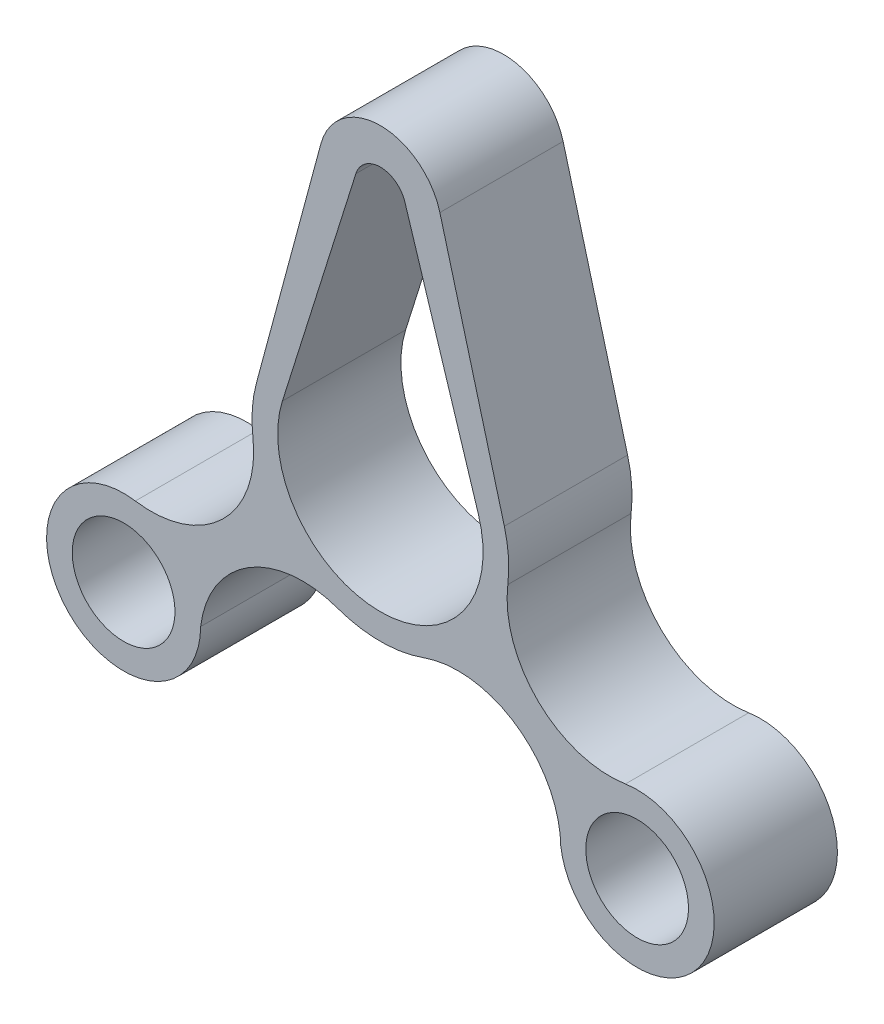
SolidWorks part; units mm, degrees
material "AISI 304"
ref_plane "Front Plane" through (0, 0, 0) normal (0, 0, 1) x (1, 0, 0)
ref_plane "Top Plane" through (0, 0, 0) normal (0, 1, 0) x (1, 0, 0)
ref_plane "Right Plane" through (0, 0, 0) normal (1, 0, 0) x (0, 0, -1)
sketch "Sketch1" plane through (0, 0, 0) normal (0, 0, 1) x (1, 0, 0)
  line L0 (0, 0) -> (0, 50) construction
  line L1 (24.1402, 6.5) -> (11.5873, 53.12)
  line L2 (4.7697, 51.5) -> (19.0788, 6)
  line L3 (-4.7697, 51.5) -> (-19.0788, 6)
  line L4 (-24.1402, 6.5) -> (-11.5873, 53.12)
  arc A0 (-19.0788, 6) -> (19.0788, 6) centre (0, 0) ccw
  arc A1 (-8.412, -23.5423) -> (8.412, -23.5423) centre (0, 0) ccw
  circle A2 centre (50, -40) radius 10
  arc A3 (35, -40) -> (47.7174, -25.1747) centre (50, -40) ccw
  arc A4 (47.7174, -25.1747) -> (24.8188, -3.0042) centre (44.6739, -5.4076) cw
  arc A5 (8.412, -23.5423) -> (35, -40) centre (15.1416, -42.3761) cw
  arc A6 (11.5873, 53.12) -> (-11.5873, 53.12) centre (0, 50) ccw
  arc A7 (4.7697, 51.5) -> (-4.7697, 51.5) centre (0, 50) ccw
  arc A8 (24.8188, -3.0042) -> (24.1402, 6.5) centre (0, 0) ccw
  arc A9 (-24.8188, -3.0042) -> (-24.1402, 6.5) centre (0, 0) cw
  arc A10 (-8.412, -23.5423) -> (-35, -40) centre (-15.1416, -42.3761) ccw
  arc A11 (-47.7174, -25.1747) -> (-24.8188, -3.0042) centre (-44.6739, -5.4076) ccw
  arc A12 (-35, -40) -> (-47.7174, -25.1747) centre (-50, -40) cw
  circle A13 centre (-50, -40) radius 10
  point P14 (0, 0)
  point P16 (25.8904, -0.2118)
  dimension "D3" = 12
  dimension "D4" = 5
  dimension "D5" = 25
  dimension "D6" = 20
  dimension "D7" = 20
  dimension "D8" = 20
  dimension "D9" = 30
  dimension "D1" = 50
  dimension "D2" = 40
  dimension "D10" = 50
extrude "Boss-Extrude1" add sketch "Sketch1" along normal blind 24
